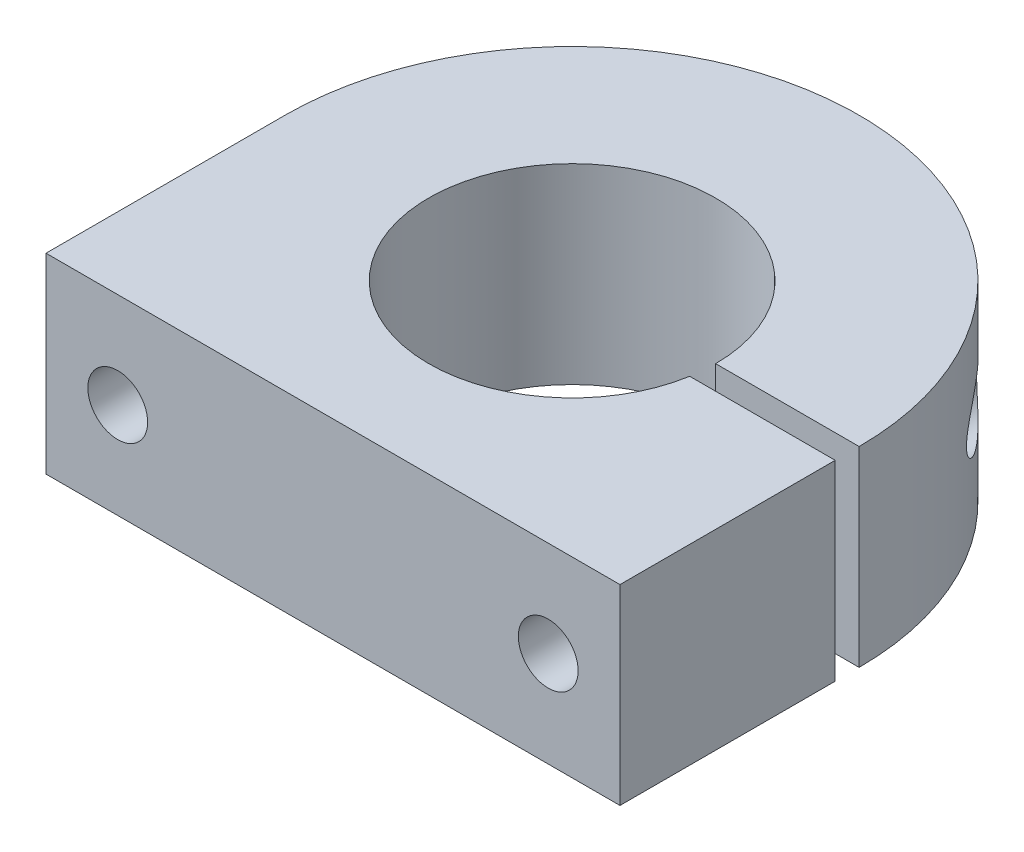
SolidWorks part; units mm, degrees
ref_plane "Front Plane" through (0, 0, 0) normal (0, 0, 1) x (1, 0, 0)
ref_plane "Top Plane" through (0, 0, 0) normal (0, 1, 0) x (1, 0, 0)
ref_plane "Right Plane" through (0, 0, 0) normal (1, 0, 0) x (0, 0, -1)
sketch "Sketch1" plane through (0, 0, 0) normal (0, 1, 0) x (1, 0, 0)
  line L0 (0, 0) -> (0, -58.7184) construction
  line L1 (-12, -10) -> (12, -10)
  line L2 (-12, -10) -> (-12, 0)
  line L3 (-34.5834, 0) -> (23.6257, 0) construction
  line L4 (12, -10) -> (12, 0)
  arc A1 (12, 0) -> (-12, 0) centre (0, 0) ccw
  dimension "D2" = 12
  dimension "D3" = 10
  dimension "D4" = 12
extrude "Boss-Extrude1" add sketch "Sketch1" along normal blind 8 contours L2 A1 L4 L1
sketch "Sketch2" plane through (0, 8, 0) normal (0, 1, 0) x (1, 0, 0)
  line L0 (-12, -10) -> (-12, 0) construction
  line L3 (-12, -10) -> (12, -10) construction
  circle A0 centre (0, 0) radius 6
  point P6 (-3.21, -10)
  point P7 (-3.21, -10)
  dimension "D3" = 12
  dimension "D1" = 12
  dimension "D2" = 10
extrude "Cut-Extrude1" cut sketch "Sketch2" against normal through all
hole_wizard "Tap Drill for M3x0.5 Tap1" positions "Sketch4" profile "Sketch5" hole size "M3x0.5" standard "ANSI Metric" end condition through all
sketch "Sketch4" plane through (0, 0, 10) normal (0, 0, 1) x (1, 0, 0)
  line L0 (0, 0) -> (0, 8)
  line L1 (-12, 0) -> (12, 0) construction
  line L2 (-12, 8) -> (12, 8) construction
  line L4 (-12, 4) -> (12, 4)
  line L5 (-12, 8) -> (-12, 0) construction
  line L6 (12, 8) -> (12, 0) construction
  point P17 (-9, 4)
  point P19 (9, 4)
  dimension "D1" = 9
  dimension "D2" = 9
sketch "Sketch5" plane through (-9, 4, 10) normal (1, 0, 0) x (0, -1, 0)
  line L0 (0, 0) -> (0, 22)
  line L1 (0, 22) -> (1.25, 22)
  line L2 (1.25, 22) -> (1.25, 0)
  line L5 (1.25, 0) -> (0, 0)
  line L11 (0, -6.35) -> (0, 107.95) construction
  dimension "Thru Hole Dia." = 2.5
  dimension "Thru Hole Depth" = 22
sketch "Sketch6" plane through (0, 8, 0) normal (0, 1, 0) x (1, 0, 0)
  line L0 (12, -10) -> (12, 0) construction
  line L1 (0, 0) -> (12, 0)
  line L2 (0, 0) -> (0, -1)
  line L3 (0, -1) -> (12, -1)
  line L4 (12, 0) -> (12, -1)
  dimension "D1" = 1
extrude "Cut-Extrude2" cut sketch "Sketch6" against normal blind 8
